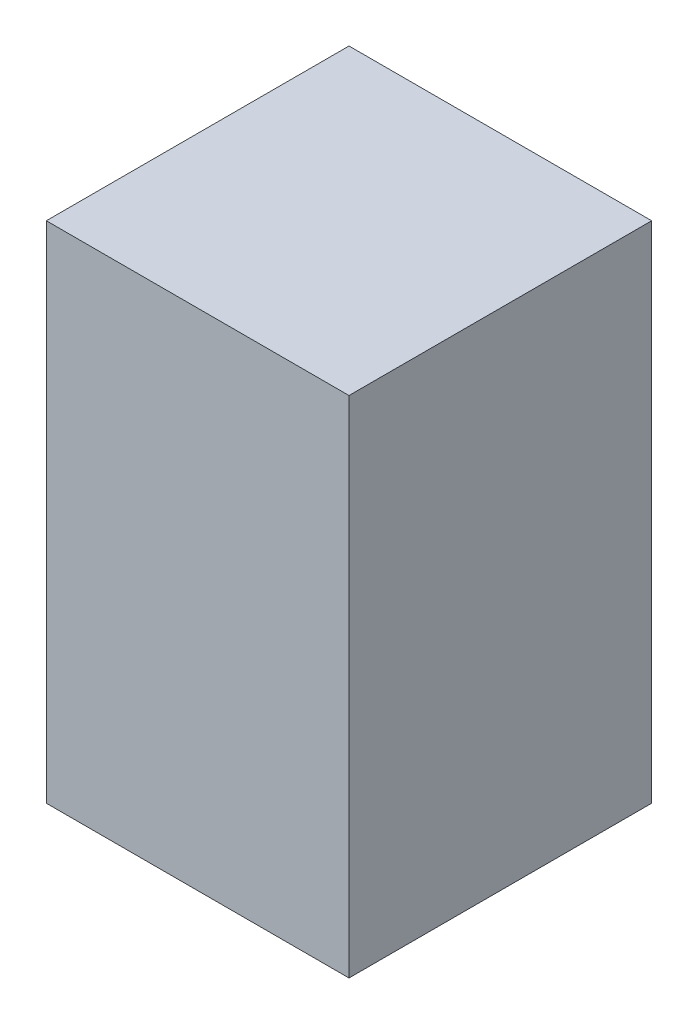
SolidWorks part; units mm, degrees
ref_plane "Front Plane" through (0, 0, 0) normal (0, 0, 1) x (1, 0, 0)
ref_plane "Top Plane" through (0, 0, 0) normal (0, 1, 0) x (1, 0, 0)
ref_plane "Right Plane" through (0, 0, 0) normal (1, 0, 0) x (0, 0, -1)
sketch "Sketch1" plane through (0, 0, 0) normal (0, 1, 0) x (1, 0, 0)
  line L1 (-1.5, 1.5) -> (1.5, 1.5)
  line L2 (-1.5, 1.5) -> (-1.5, -1.5)
  line L3 (-1.5, -1.5) -> (1.5, -1.5)
  line L4 (1.5, 1.5) -> (1.5, -1.5)
  line L5 (-1.5, 1.5) -> (1.5, -1.5) construction
  line L6 (-1.5, -1.5) -> (1.5, 1.5) construction
  point P0 (0, 0)
  dimension "D1" = 3
extrude "Boss-Extrude1" add sketch "Sketch1" along normal blind 5
